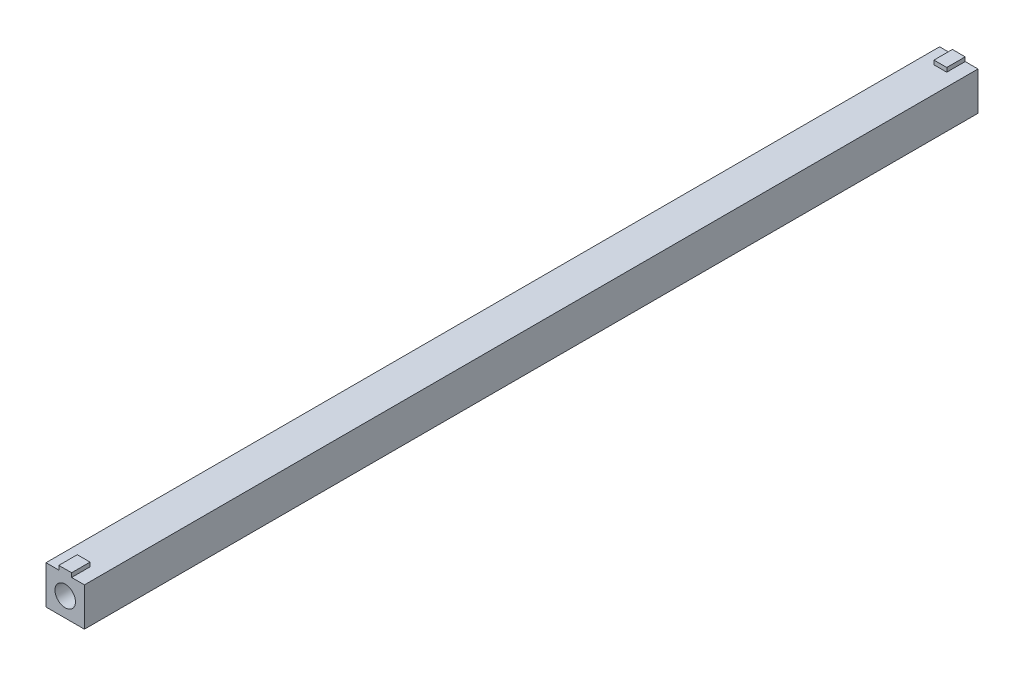
SolidWorks part; units mm, degrees
material "6061 合金"
ref_plane "前视基准面" through (0, 0, 0) normal (0, 0, 1) x (1, 0, 0)
ref_plane "上视基准面" through (0, 0, 0) normal (0, 1, 0) x (1, 0, 0)
ref_plane "右视基准面" through (0, 0, 0) normal (1, 0, 0) x (0, 0, -1)
sketch "草图1" plane through (0, 0, 0) normal (0, 0, 1) x (1, 0, 0)
  line L1 (-15, 15) -> (15, 15)
  line L2 (-15, 15) -> (-15, -15)
  line L3 (-15, -15) -> (15, -15)
  line L4 (15, 15) -> (15, -15)
  line L5 (-15, 15) -> (15, -15) construction
  line L6 (-15, -15) -> (15, 15) construction
  circle A0 centre (0, 0) radius 8
  point P0 (0, 0)
  dimension "D2" = 16
  dimension "D1" = 30
extrude "凸台-拉伸1" add sketch "草图1" along normal blind 697.8
sketch "草图2" plane through (0, 0, 697.8) normal (0, 0, 1) x (1, 0, 0)
  line L0 (15, 15) -> (-15, 15) construction
  line L1 (-5, 15) -> (5, 15)
  line L2 (-5, 15) -> (-5, 18.2)
  line L3 (-5, 18.2) -> (5, 18.2)
  line L4 (5, 15) -> (5, 18.2)
  point P6 (0, 18.2)
  dimension "D1" = 3.2
  dimension "D2" = 10
extrude "凸台-拉伸2" add sketch "草图2" against normal blind 14.4
ref_plane "基准面1" through (0, 0, 348.9) normal (0, 0, 1) x (1, 0, 0)
mirror "镜向1" about plane through (0, 0, 348.9) normal (0, 0, 1) of "凸台-拉伸2"
